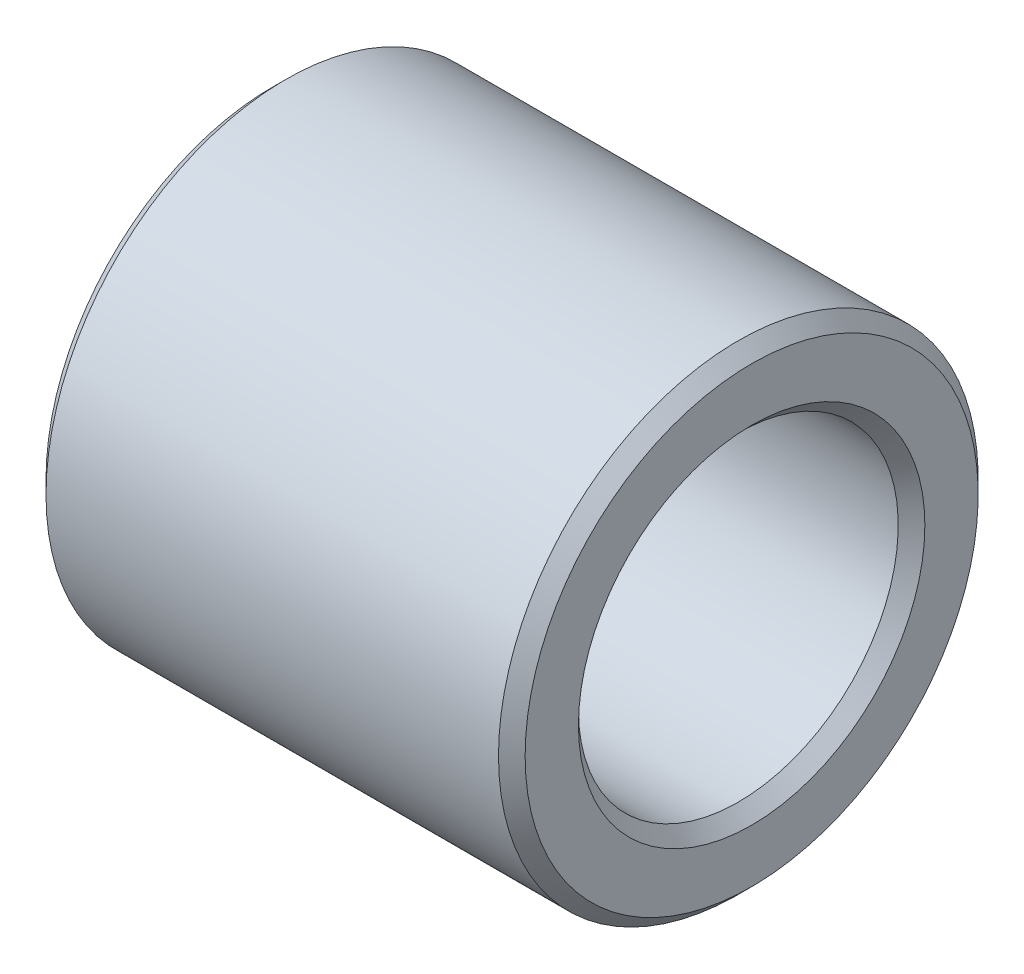
SolidWorks part; units mm, degrees
ref_plane "Plan de face" through (0, 0, 0) normal (0, 0, 1) x (1, 0, 0)
ref_plane "Plan de dessus" through (0, 0, 0) normal (0, 1, 0) x (1, 0, 0)
ref_plane "Plan de droite" through (0, 0, 0) normal (1, 0, 0) x (0, 0, -1)
sketch "Esquisse1" plane through (0, 0, 0) normal (0, 0, 1) x (1, 0, 0)
  line L0 (-10.6551, 0) -> (91.9494, 0) construction
  line L1 (0, 8.5) -> (0.5, 9)
  line L2 (0.5, 9) -> (17.48, 9)
  line L3 (0, 8.5) -> (0, 6.5)
  line L4 (0.5, 6) -> (17.48, 6)
  line L5 (17.98, 8.5) -> (17.98, 6.5)
  line L6 (0, 6.5) -> (0.5, 6)
  line L7 (17.48, 6) -> (17.98, 6.5)
  line L8 (17.48, 9) -> (17.98, 8.5)
  point P3 (0, 9)
  point P4 (17.98, 6)
  point P5 (0, 6)
  point P6 (17.98, 9)
  dimension "D1" = 17.98
  dimension "D2" = 12
  dimension "D3" = 18
  dimension "D6" = 0.5
  dimension "D7" = 0.5
  dimension "D8" = 0.5
  dimension "D9" = 0.5
revolve "Révolution1" add sketch "Esquisse1" angle 360 about L0
